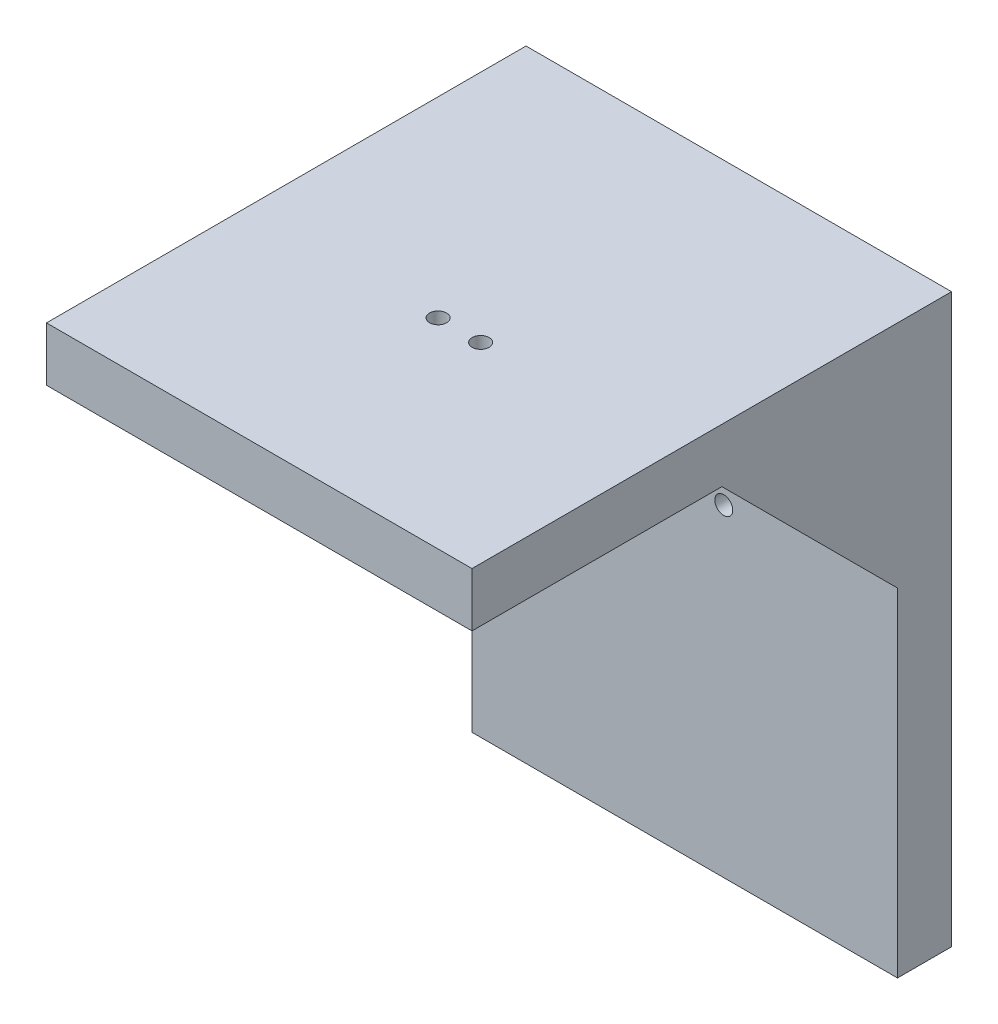
SolidWorks part; units mm, degrees
ref_plane "Front Plane" through (0, 0, 0) normal (0, 0, 1) x (1, 0, 0)
ref_plane "Top Plane" through (0, 0, 0) normal (0, 1, 0) x (1, 0, 0)
ref_plane "Right Plane" through (0, 0, 0) normal (1, 0, 0) x (0, 0, -1)
sketch "Sketch1" plane through (0, 0, 0) normal (0, 0, 1) x (1, 0, 0)
  line L1 (0, 0) -> (150, 0)
  line L2 (0, 0) -> (0, 200)
  line L3 (0, 200) -> (150, 200)
  line L4 (150, 0) -> (150, 200)
  dimension "D1" = 200
  dimension "D2" = 150
extrude "Plate" add sketch "Sketch1" along normal blind 19.05 contours L3 L4 L1 L2
ref_plane "Plane1" through (75, 0, 0) normal (-1, 0, 0) x (0, 0, 1)
sketch "Sketch2" plane through (0, 0, 19.05) normal (0, 0, 1) x (1, 0, 0)
  line L0 (150, 0) -> (150, 200) construction
  line L1 (0, 200) -> (150, 200)
  line L2 (0, 200) -> (0, 180.95)
  line L3 (0, 180.95) -> (150, 180.95)
  line L4 (150, 200) -> (150, 180.95)
  dimension "D1" = 19.05
extrude "Boss-Extrude1" add sketch "Sketch2" along normal blind 150
sketch "Sketch3" plane through (0, 0, 0) normal (-1, 0, 0) x (0, 0, 1)
  line L0 (0, 200) -> (0, 100)
  line L1 (0, 0) -> (0, 200) construction
  line L2 (0, 100) -> (100, 200)
  line L3 (169.05, 200) -> (0, 200) construction
  line L4 (100, 200) -> (0, 200)
  dimension "D1" = 100
  dimension "D2" = 100
extrude "Boss-Extrude2" add sketch "Sketch3" against normal blind 19.05
mirror "Mirror1" about plane through (75, 0, 0) normal (-1, 0, 0) of "Boss-Extrude2"
sketch "Sketch4" plane through (0, 0, 19.05) normal (0, 0, 1) x (1, 0, 0)
  circle A0 centre (61.25, 171.25) radius 3.175
  circle A1 centre (61.25, 142.5) radius 3.175
  circle A2 centre (61.25, 113.75) radius 3.175
  dimension "D1" = 6.35
extrude "Cut-Extrude1" cut sketch "Sketch4" against normal through all both and the other way through all
mirror "Mirror2" about plane through (75, 0, 0) normal (-1, 0, 0) of "Cut-Extrude1"
sketch "Sketch6" plane through (0, 180.95, 0) normal (0, -1, 0) x (1, 0, 0)
  line L0 (0, 169.05) -> (0, 80.95) construction
  line L1 (150, 169.05) -> (150, 80.95) construction
  line L2 (0, 169.05) -> (150, 169.05) construction
  circle A0 centre (67.5, 98.5) radius 3
  circle A1 centre (82.5, 98.5) radius 3
  dimension "D1" = 6
  dimension "D2" = 6
  dimension "D4" = 67.5
  dimension "D5" = 70.55
  dimension "D3" = 67.5
extrude "Cut-Extrude2" cut sketch "Sketch6" against normal through all
